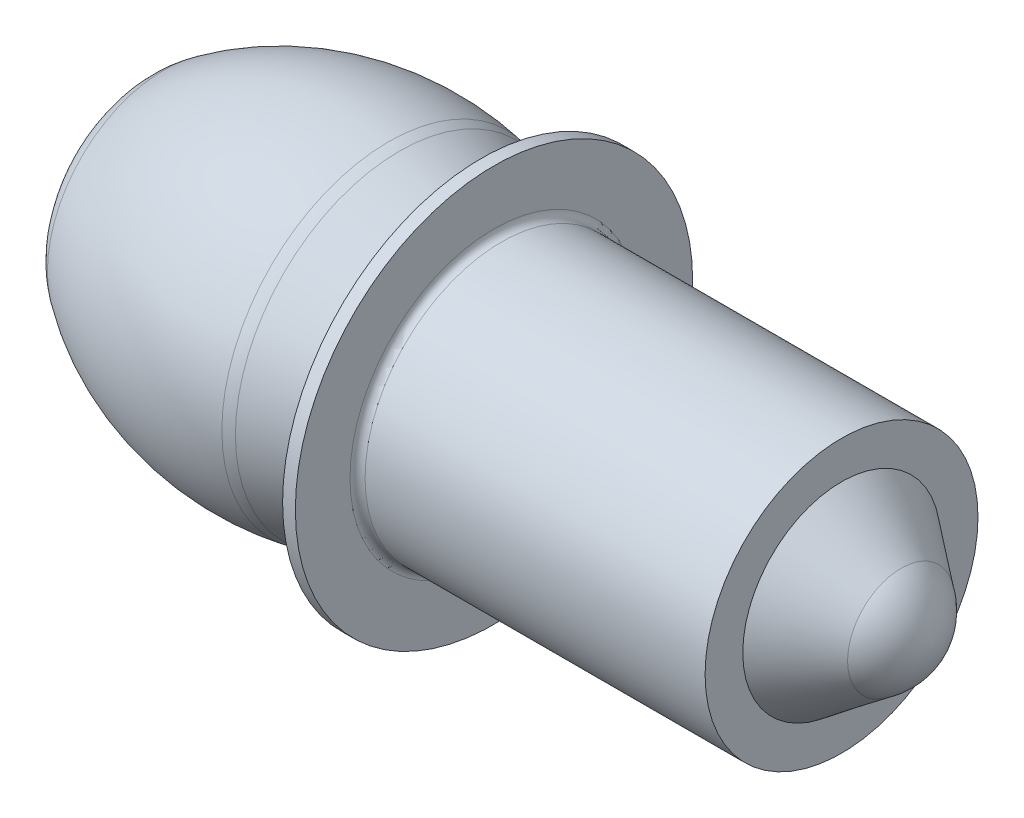
SolidWorks part; units mm, degrees
ref_plane "Front Plane" through (0, 0, 0) normal (0, 0, 1) x (1, 0, 0)
ref_plane "Top Plane" through (0, 0, 0) normal (0, 1, 0) x (1, 0, 0)
ref_plane "Right Plane" through (0, 0, 0) normal (1, 0, 0) x (0, 0, -1)
sketch "Sketch1" plane through (0, 0, 0) normal (0, 0, 1) x (1, 0, 0)
  line L0 (13.0324, 2.0955) -> (10.2768, 1.1662)
  line L1 (13.0324, 0) -> (13.462, 0)
  line L2 (0.2666, 6.3038) -> (0.9067, 5.3694)
  line L3 (0.1554, 6.6929) -> (0.1554, 6.6627)
  line L4 (0.1554, 6.6929) -> (1.27, 6.6929)
  line L6 (13.0324, 2.0955) -> (13.0324, 0)
  line L7 (13.462, 1.8415) -> (13.462, 0)
  line L8 (0, 6.6929) -> (28.2194, 6.6929)
  line L9 (25.1714, 2.0955) -> (25.1714, 3.3655)
  line L12 (25.1714, 2.0955) -> (25.1714, 3.3655)
  line L13 (25.1714, 3.3655) -> (27.178, 4.8895)
  line L14 (25.1714, 2.0955) -> (13.716, 2.0955)
  arc A0 (27.178, 4.8895) -> (28.2194, 6.6929) centre (25.9228, 6.8167) ccw
  arc A1 (13.716, 2.0955) -> (13.462, 1.8415) centre (13.716, 1.8415) ccw
  arc A2 (2.3389, 2.7686) -> (9.9129, 1.0728) centre (8.1455, 10.9413) ccw
  arc A3 (10.2768, 1.1662) -> (9.9129, 1.0728) centre (9.4651, 3.573) cw
  arc A4 (2.3389, 2.7686) -> (1.3107, 4.3865) centre (3.81, 4.8392) cw
  arc A5 (1.3107, 4.3865) -> (0.9067, 5.3694) centre (-1.1887, 3.9339) ccw
  arc A6 (0.1554, 6.6627) -> (0.2666, 6.3038) centre (0.7904, 6.6627) ccw
  point P24 (1.27, 3.6449)
  point P27 (0.1554, 6.466)
  dimension "D6" = 0.254
  dimension "D4" = 2.54
  dimension "D7" = 2.54
  dimension "D2" = 2.54
  dimension "D9" = 0.635
  dimension "D1" = 1.27
  dimension "D3" = 3.048
  dimension "D5" = 1.27
  dimension "D8" = 0.2269
revolve "Revolve7" add sketch "Sketch1" angle 360 about L8
